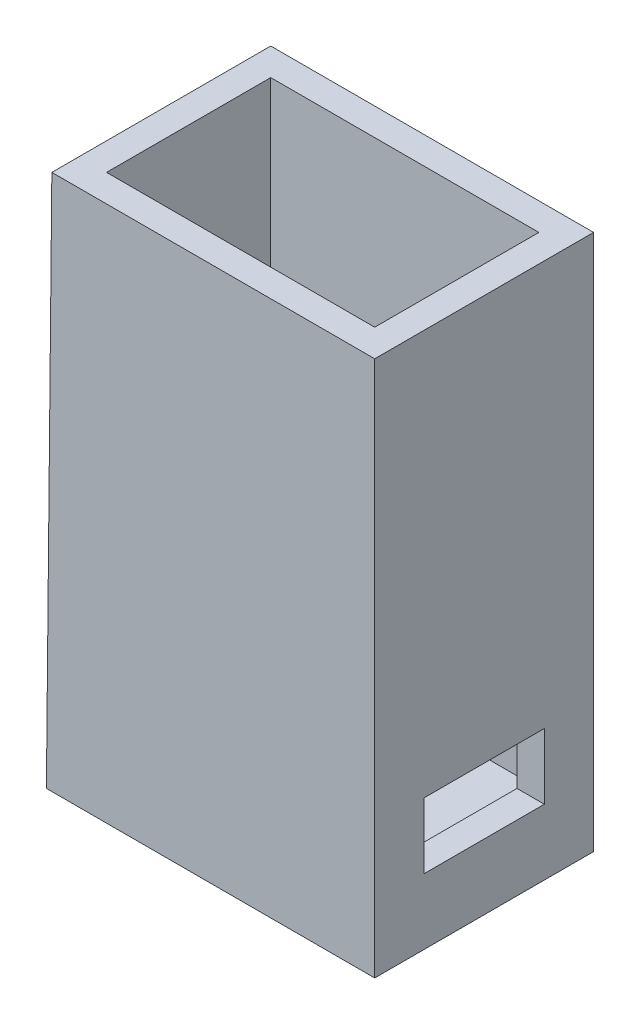
SolidWorks part; units mm, degrees
ref_plane "Front Plane" through (0, 0, 0) normal (0, 0, 1) x (1, 0, 0)
ref_plane "Top Plane" through (0, 0, 0) normal (0, 1, 0) x (1, 0, 0)
ref_plane "Right Plane" through (0, 0, 0) normal (1, 0, 0) x (0, 0, -1)
sketch "Sketch2" plane through (0, 0, 0) normal (0, 0, 1) x (1, 0, 0)
  line L0 (0, 0) -> (0.6321, 62.23)
  line L1 (0.6321, 62.23) -> (3.8071, 62.23)
  line L2 (3.8071, 62.23) -> (3.8071, 6.35)
  line L3 (3.8071, 6.35) -> (34.925, 6.35)
  line L4 (34.925, 6.35) -> (34.925, 62.23)
  line L5 (34.925, 62.23) -> (38.1, 62.23)
  line L6 (38.1, 62.23) -> (38.1, 0)
  line L7 (38.1, 0) -> (0, 0)
  dimension "D1" = 38.1
  dimension "D2" = 3.175
  dimension "D3" = 3.175
  dimension "D4" = 62.23
  dimension "D5" = 55.88
  dimension "D6" = 55.88
extrude "Boss-Extrude1" add sketch "Sketch2" along normal blind 25.4 contours L0 L1 L2 L3 L4 L5 L6 L7
sketch "Sketch3" plane through (38.1, 0, 0) normal (1, 0, 0) x (0, 0, -1)
  line L0 (-12.7, 62.23) -> (-12.7, 0) construction
  line L1 (-25.4, 62.23) -> (0, 62.23) construction
  line L2 (-25.4, 0) -> (0, 0) construction
  line L3 (-12.7, 15.24) -> (-12.7, 7.62) construction
  line L4 (-19.685, 15.24) -> (-5.715, 15.24)
  line L5 (-19.685, 15.24) -> (-19.685, 7.62)
  line L6 (-19.685, 7.62) -> (-5.715, 7.62)
  line L7 (-5.715, 15.24) -> (-5.715, 7.62)
  dimension "D1" = 54.61
  dimension "D2" = 7.62
  dimension "D3" = 13.97
extrude "Cut-Extrude1" cut sketch "Sketch3" against normal through all contours L4 L7 L6 L5
sketch "Sketch4" plane through (0, 6.35, 0) normal (0, 1, 0) x (1, 0, 0)
  line L0 (3.8071, -3.175) -> (34.925, -3.175)
  line L1 (3.8071, -25.4) -> (3.8071, 0) construction
  line L2 (34.925, -25.4) -> (34.925, 0) construction
  line L3 (34.925, -3.175) -> (34.925, 0)
  line L4 (34.925, -25.4) -> (34.925, 0) construction
  line L5 (34.925, 0) -> (3.8071, 0)
  line L6 (3.8071, 0) -> (3.8071, -3.175)
  line L8 (3.8071, -25.4) -> (34.925, -25.4)
  line L9 (3.8071, -25.4) -> (3.8071, -22.225)
  line L10 (3.8071, -22.225) -> (34.925, -22.225)
  line L11 (34.925, -25.4) -> (34.925, -22.225)
  dimension "D1" = 3.175
  dimension "D2" = 3.175
extrude "Boss-Extrude2" add sketch "Sketch4" along normal blind 55.88
equation "\"modulus\"= 435000"
equation "\"safety_factor\"= 3.5"
equation "\"tensile\"= 5"
equation "\"axial\"= 7.5"
equation "\"yield\"= 7250"
equation "\"width\"= 0.50"
equation "\"base\"= 0.25"
equation "\"deflection\"= 1 / 64"
equation "\"length\"= 2.20"
equation "\"area\"= 0.125"
